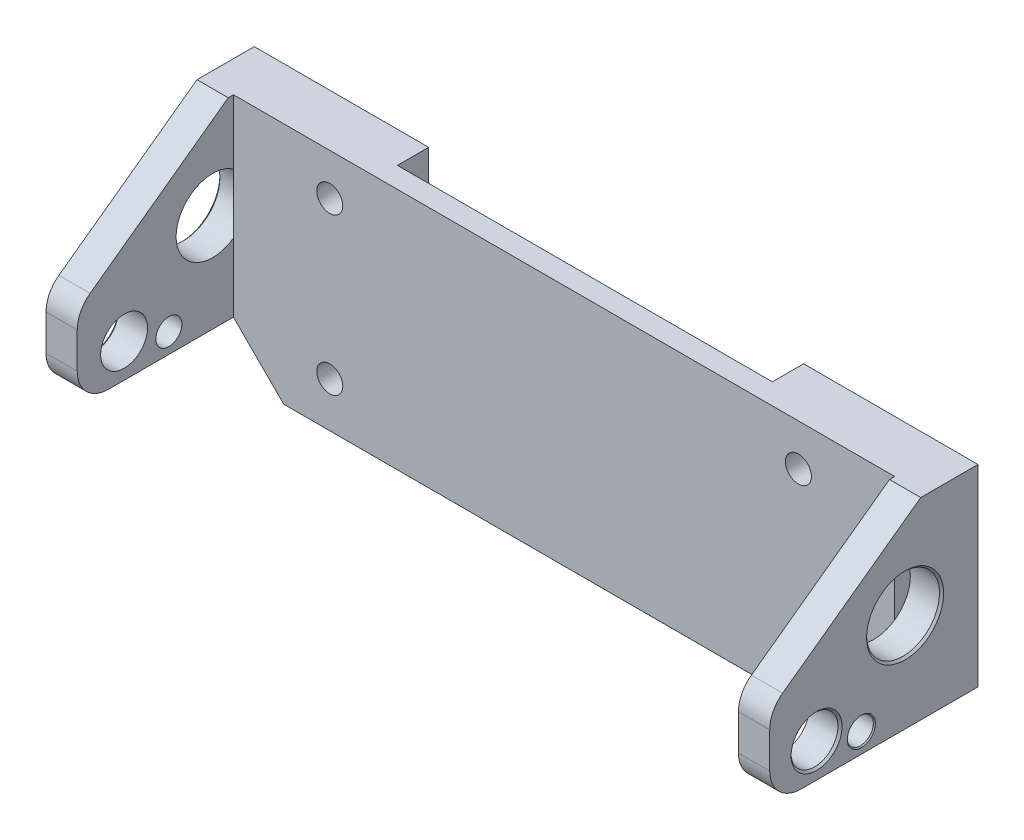
SolidWorks part; units mm, degrees
material "AISI 304"
ref_plane "前视基准面" through (0, 0, 0) normal (0, 0, 1) x (1, 0, 0)
ref_plane "上视基准面" through (0, 0, 0) normal (0, 1, 0) x (1, 0, 0)
ref_plane "右视基准面" through (0, 0, 0) normal (1, 0, 0) x (0, 0, -1)
sketch "草图1" plane through (0, 0, 0) normal (0, 0, 1) x (1, 0, 0)
  line L0 (0, 12) -> (0, -12) construction
  line L1 (-31.75, 12) -> (31.75, 12)
  line L2 (-31.75, 12) -> (-31.75, -12)
  line L3 (-31.75, -12) -> (31.75, -12)
  line L4 (31.75, 12) -> (31.75, -12)
  dimension "D1" = 24
  dimension "D2" = 63.5
extrude "拉伸1" add sketch "草图1" along normal blind 5.5
sketch "草图2" plane through (0, -12, 0) normal (0, -1, 0) x (1, 0, 0)
  line L0 (-31.75, 0) -> (31.75, 0) construction
  line L1 (-17.5, 0) -> (17.5, 0)
  line L2 (-17.5, 0) -> (-17.5, 3)
  line L3 (-17.5, 3) -> (17.5, 3)
  line L4 (17.5, 0) -> (17.5, 3)
  line L5 (0, 0) -> (0, 3) construction
  dimension "D1" = 3
  dimension "D2" = 35
extrude "拉伸2" cut sketch "草图2" against normal up to surface (24 mm away) up to face at (0, 12, 2.75)
sketch "草图3" plane through (0, 0, 0) normal (0, 0, -1) x (-1, 0, 0)
  line L0 (0, 8) -> (0, -7) construction
  line L1 (-22.5, 8) -> (22.5, 8)
  line L2 (-22.5, 8) -> (-22.5, -7)
  line L3 (-22.5, -7) -> (22.5, -7)
  line L4 (22.5, 8) -> (22.5, -7)
  line L5 (17.5, 12) -> (-17.5, 12) construction
  dimension "D1" = 45
  dimension "D2" = 15
  dimension "D3" = 4
hole_wizard "M3 螺纹孔1" positions "3D草图1" profile "草图4" tap size "M3" standard "GB"
sketch3d "3D草图1"
  point P0 (22.5, 8, 0)
  point P3 (22.5, -7, 0)
  point P6 (-22.5, -7, 0)
  point P9 (-22.5, 8, 0)
sketch "草图4" plane through (22.5, 8, 0) normal (1, 0, 0) x (0, 1, 0)
  line L0 (0, 0) -> (0, 8.2511)
  line L1 (0, 8.2511) -> (1.25, 7.5)
  line L2 (1.25, 7.5) -> (1.25, 0)
  line L5 (1.25, 0) -> (0, 0)
  line L10 (0, 8.2511) -> (-1.25, 7.5) construction
  line L11 (0, -6.35) -> (0, 107.95) construction
  dimension "螺纹孔钻头直径" = 2.5
  dimension "螺纹孔钻头深度" = 7.5
  dimension "导头角度" = 118
cosmetic thread "孔螺蚊线1" parameters "D1"=6, "D2"=3
cosmetic thread "孔螺蚊线2" parameters "D1"=6, "D2"=3
cosmetic thread "孔螺蚊线3" parameters "D1"=6, "D2"=3
cosmetic thread "孔螺蚊线4" parameters "D1"=6, "D2"=3
chamfer "倒角1" distance 0.5 angle 45 4 edges at (-23.75, 8, 0) (-23.75, -7, 0) (21.25, -7, 0) (21.25, 8, 0)
chamfer "倒角2" distance 0.5 angle 45 4 edges at (-21.25, 8, 5.5) (-21.25, -7, 5.5) (23.75, 8, 5.5) (23.75, -7, 5.5)
chamfer "倒角3" distance 5.5 angle 45 2 edges at (-31.75, -12, 2.75) (31.75, -12, 2.75)
sketch "草图7" plane through (31.75, 0, 0) normal (1, 0, 0) x (0, 0, -1)
  line L1 (0, 12) -> (-20, 12)
  line L2 (0, 12) -> (0, -6.5)
  line L3 (0, -6.5) -> (-20, -6.5)
  line L4 (-20, 12) -> (-20, -6.5)
  dimension "D1" = 20
  dimension "D2" = 18.5
extrude "凸台-拉伸1" add sketch "草图7" along normal blind 3
sketch "草图8" plane through (34.75, 0, 0) normal (1, 0, 0) x (0, 0, -1)
  line L0 (0, -6.5) -> (0, 12) construction
  line L1 (0, 12) -> (-20, 12) construction
  circle A0 centre (-7, 2.95) radius 3.5
  dimension "D1" = 7
  dimension "D2" = 9.05
  dimension "D3" = 7
extrude "切除-拉伸1" cut sketch "草图8" against normal up to surface (3 mm away) up to face at (31.75, 0.4375, 12.75)
sketch "草图9" plane through (34.75, 0, 0) normal (1, 0, 0) x (0, 0, -1)
  line L1 (0, -6.5) -> (0, 12) construction
  line L2 (0, 12) -> (-20, 12) construction
  circle A0 centre (-15.5, -3.25) radius 2.25
  dimension "D1" = 4.5
  dimension "D2" = 15.5
  dimension "D3" = 15.25
extrude "切除-拉伸2" cut sketch "草图9" against normal blind 87
sketch "草图10" plane through (31.75, 0, 0) normal (1, 0, 0) x (0, 0, -1)
  line L0 (-20, 1.4651) -> (-20, 12)
  line L1 (-20, 12) -> (-5.5, 12)
  line L3 (-20, 1.4651) -> (-5.5, 12)
  line L6 (0, 12) -> (-20, 12) construction
  dimension "D1" = 36
extrude "切除-拉伸4" cut sketch "草图10" along normal blind 10 contours L1 L3 L0
mirror "镜向2" about plane through (0, 0, 0) normal (1, 0, 0) of "切除-拉伸4", "切除-拉伸2", "切除-拉伸1", "凸台-拉伸1"
fillet "圆角1" radius 3 4 edges at (33.25, -6.5, 20) (33.25, 1.4651, 20) (-33.25, 1.4651, 20) (-33.25, -6.5, 20)
chamfer "倒角5" distance 0.2 angle 45 4 edges at (-34.75, 2.95, 3.5) (-34.75, -3.25, 13.25) (34.75, 2.95, 3.5) (34.75, -3.25, 13.25)
fillet "圆角3" radius 2 1 edges at (0, -12, 5.5)
sketch "草图11" plane through (-34.75, 0, 0) normal (-1, 0, 0) x (0, 0, 1)
  line L0 (17, -6.5) -> (0, -6.5) construction
  line L1 (0, -6.5) -> (0, 12) construction
  circle A0 centre (11.2, -4.6) radius 1.25
  dimension "D1" = 1.9
  dimension "D2" = 11.2
  dimension "D3" = 2.5
extrude "切除-拉伸5" cut sketch "草图11" against normal blind 96
chamfer "倒角6" distance 0.1 angle 45 2 edges at (34.75, -4.6, 12.45) (-34.75, -4.6, 12.45)
sketch "草图12" plane through (0, 0, 3) normal (0, 0, -1) x (-1, 0, 0)
  line L1 (-17.5, -12) -> (17.5, -12)
  line L2 (-17.5, -12) -> (-17.5, 12)
  line L3 (-17.5, 12) -> (17.5, 12)
  line L4 (17.5, -12) -> (17.5, 12)
extrude "凸台-拉伸2" add sketch "草图12" along normal blind 3
sketch "草图13" plane through (0, 0, 0) normal (0, 0, -1) x (-1, 0, 0)
  line L0 (-34.75, 12) -> (34.75, 12) construction
  line L1 (-18, 12) -> (18, 12)
  line L2 (-18, 12) -> (-18, -12)
  line L3 (-18, -12) -> (18, -12)
  line L4 (18, 12) -> (18, -12)
  line L5 (26.25, -12) -> (-26.25, -12) construction
  dimension "D1" = 18
  dimension "D2" = 36
extrude "切除-拉伸6" cut sketch "草图13" against normal blind 3
sketch "草图14" plane through (0, 0, 5.5) normal (0, 0, 1) x (1, 0, 0)
  line L0 (31.75, -6.5) -> (25.25, -13)
  line L1 (-31.75, -6.5) -> (-25.25, -13)
  line L3 (31.75, -6.5) -> (31.75, 12)
  line L4 (31.75, 12) -> (-31.75, 12)
  line L5 (-31.75, 12) -> (-31.75, -6.5)
  line L6 (-25.25, -13) -> (25.25, -13)
  dimension "D1" = 25
  dimension "D2" = 135
  dimension "D3" = 135
extrude "切除-拉伸7" cut sketch "草图14" against normal blind 0.5
